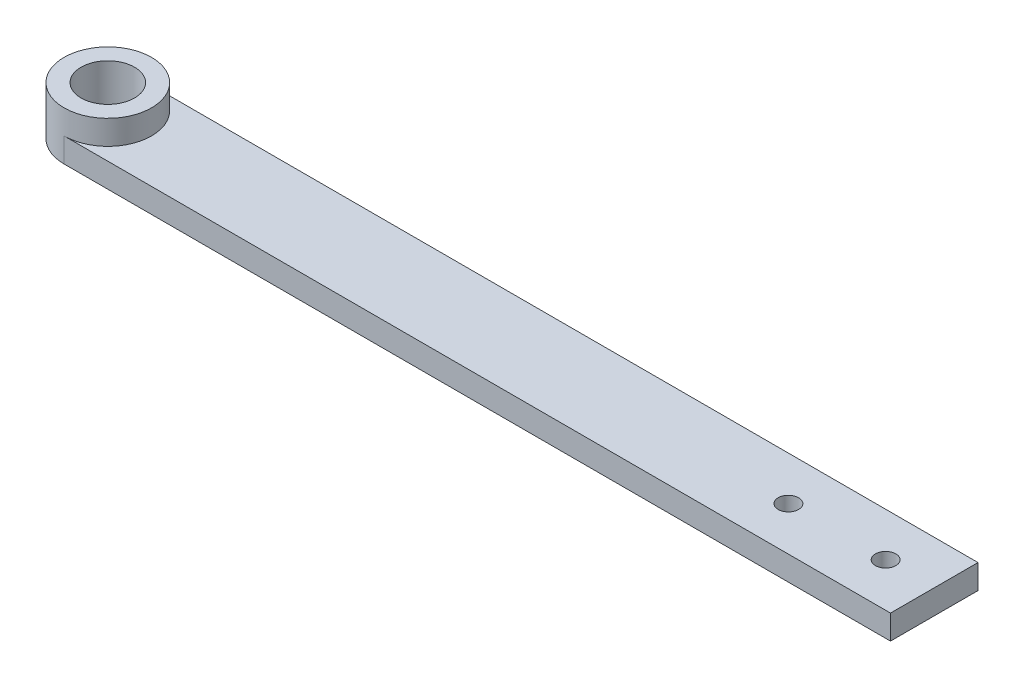
SolidWorks part; units mm, degrees
ref_plane "Front Plane" through (0, 0, 0) normal (0, 0, 1) x (1, 0, 0)
ref_plane "Top Plane" through (0, 0, 0) normal (0, 1, 0) x (1, 0, 0)
ref_plane "Right Plane" through (0, 0, 0) normal (1, 0, 0) x (0, 0, -1)
sketch "Sketch1" plane through (0, 0, 0) normal (0, 1, 0) x (1, 0, 0)
  line L0 (0, 0) -> (-170, 0)
  line L1 (-170, -18) -> (0, -18)
  line L2 (0, -18) -> (0, 0)
  arc A0 (-170, 0) -> (-170, -18) centre (-170, -9) ccw
  dimension "D1" = 9
  dimension "D2" = 170
extrude "Boss-Extrude1" add sketch "Sketch1" along normal blind 5
sketch "Sketch2" plane through (0, 5, 0) normal (0, 1, 0) x (1, 0, 0)
  circle A0 centre (-170, -9) radius 9
  dimension "D1" = 18
extrude "Boss-Extrude2" add sketch "Sketch2" along normal blind 5
sketch "Sketch3" plane through (0, 10, 0) normal (0, 1, 0) x (1, 0, 0)
  circle A0 centre (-170, -9) radius 5.5
  dimension "D1" = 11
extrude "Cut-Extrude1" cut sketch "Sketch3" against normal through all
sketch "Sketch4" plane through (0, 5, 0) normal (0, 1, 0) x (1, 0, 0)
  line L0 (0, 0) -> (-170, 0) construction
  line L1 (0, -18) -> (0, 0) construction
  circle A0 centre (-10, -9) radius 2.1
  circle A1 centre (-30, -9) radius 2.1
  point P6 (0, 0)
  dimension "D1" = 4.2
  dimension "D2" = 9
  dimension "D3" = 10
  dimension "D4" = 20
extrude "Cut-Extrude2" cut sketch "Sketch4" against normal through all
